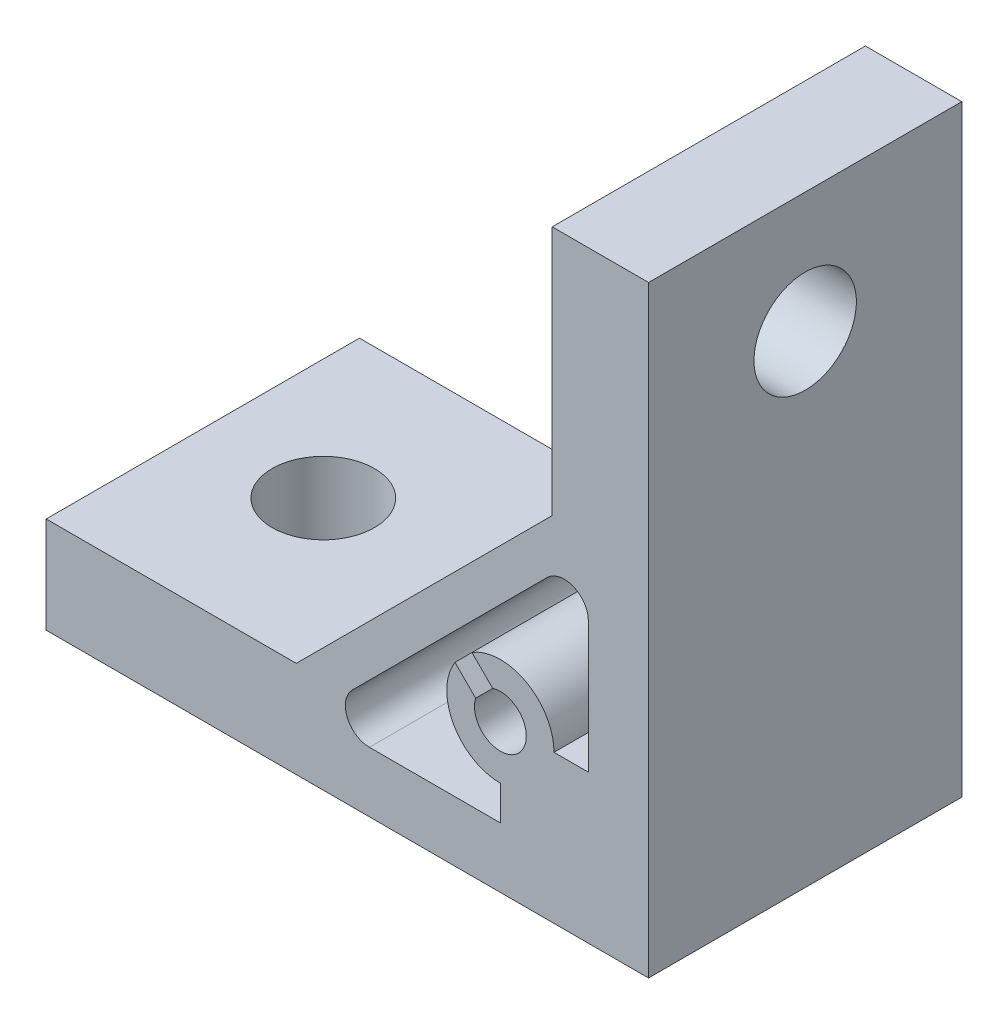
SolidWorks part; units mm, degrees
ref_plane "前视基准面" through (0, 0, 0) normal (0, 0, 1) x (1, 0, 0)
ref_plane "上视基准面" through (0, 0, 0) normal (0, 1, 0) x (1, 0, 0)
ref_plane "右视基准面" through (0, 0, 0) normal (1, 0, 0) x (0, 0, -1)
sketch "草图1" plane through (0, 0, 0) normal (0, 0, 1) x (1, 0, 0)
  line B0 (0, 0) -> (50, 0)
  line B1 (50, 0) -> (50, 50)
  line B2 (0, 8) -> (20.7574, 8)
  line B3 (42, 29.2426) -> (42, 50)
  line B4 (0, 8) -> (0, 0)
  line B5 (42, 50) -> (50, 50)
  line B6 (37.0613, 14.3529) -> (35.341, 16.0733)
  line B7 (35.6471, 12.9387) -> (33.9267, 14.659)
  line B8 (25.4142, 8.4142) -> (41.5858, 24.5858)
  line B9 (20.7574, 8) -> (42, 29.2426)
  line B10 (26.8284, 5) -> (37.7, 5)
  line B11 (45, 23.1716) -> (45, 12.3)
  line B12 (37.7, 5) -> (37.7, 7.85)
  line B13 (42.15, 12.3) -> (45, 12.3)
  arc B14 (33.9267, 14.659) -> (37.7, 7.85) centre (37.7, 12.3) ccw
  arc B15 (42.15, 12.3) -> (35.341, 16.0733) centre (37.7, 12.3) ccw
  arc B16 (35.6471, 12.9387) -> (37.0613, 14.3529) centre (37.7, 12.3) ccw
  arc B17 (25.4142, 8.4142) -> (26.8284, 5) centre (26.8284, 7) ccw
  arc B18 (45, 23.1716) -> (41.5858, 24.5858) centre (43, 23.1716) ccw
sketch_block_instance "A$C19004297-1"
sketch_block "A$C19004297"
extrude "凸台-拉伸1" add sketch "草图1" along normal mid plane 26
sketch "草图3" plane through (0, 8, 0) normal (0, 1, 0) x (1, 0, 0)
  line L0 (0, -13) -> (0, 13) construction
  circle A0 centre (10, 0) radius 4.25
  dimension "D1" = 10
extrude "切除-拉伸1" cut sketch "草图3" against normal through all
sketch "草图4" plane through (6.3787, -6.3787, 0) normal (-0.7071, 0.7071, 0) x (0, 0, 1)
  line L0 (13, 35.3553) -> (-13, 35.3553) construction
  line L1 (13, 50.3762) -> (13, 20.3345) construction
  line L2 (-13, 50.3762) -> (-13, 20.3345) construction
ref_plane "基准面2" through (25, 25, 0) normal (-0.7071, -0.7071, 0) x (0, 0, 1)
mirror "镜向1" about plane through (25, 25, 0) normal (-0.7071, -0.7071, 0) of "切除-拉伸1"
